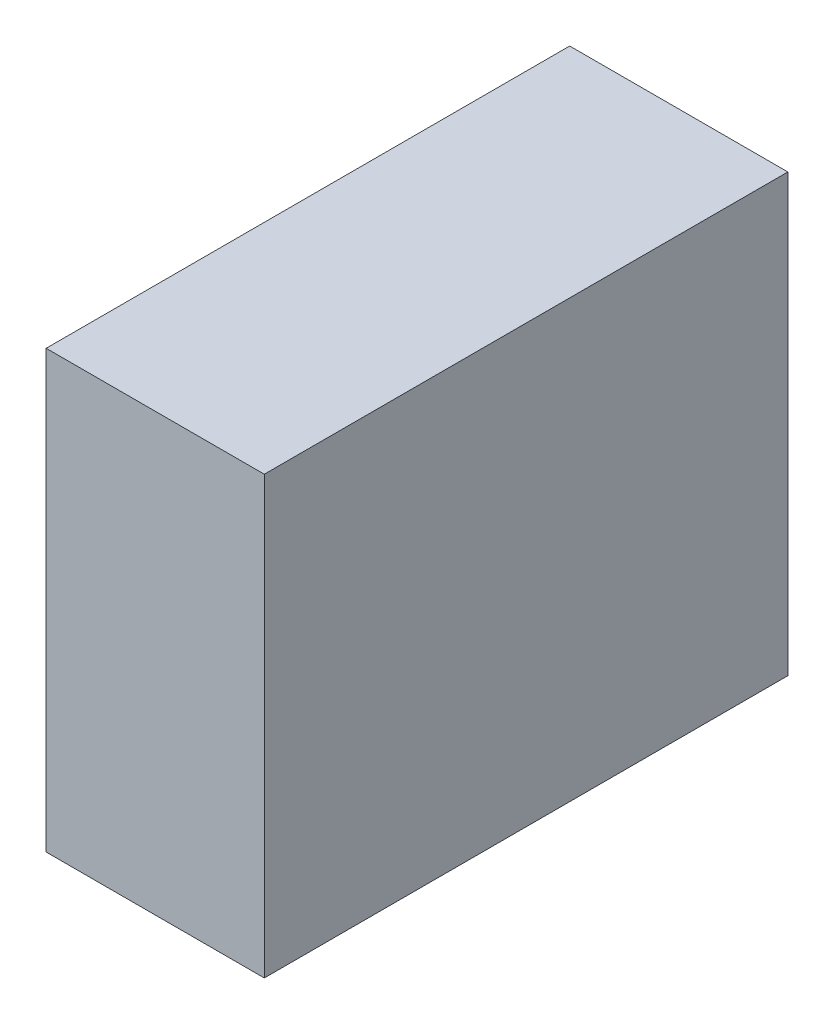
SolidWorks part; units mm, degrees
ref_plane "Front Plane" through (0, 0, 0) normal (0, 0, 1) x (1, 0, 0)
ref_plane "Top Plane" through (0, 0, 0) normal (0, 1, 0) x (1, 0, 0)
ref_plane "Right Plane" through (0, 0, 0) normal (1, 0, 0) x (0, 0, -1)
other "Configuration Table"
sketch "Sketch1" plane through (0, 0, 0) normal (0, 0, 1) x (1, 0, 0)
  line L1 (370, 200) -> (420, 200)
  line L2 (370, 200) -> (370, 300)
  line L3 (370, 300) -> (420, 300)
  line L4 (420, 200) -> (420, 300)
extrude "OVEN_pano_surucu_mentese_2_1" add sketch "Sketch1" against normal blind 120 from offset 128 separate body
